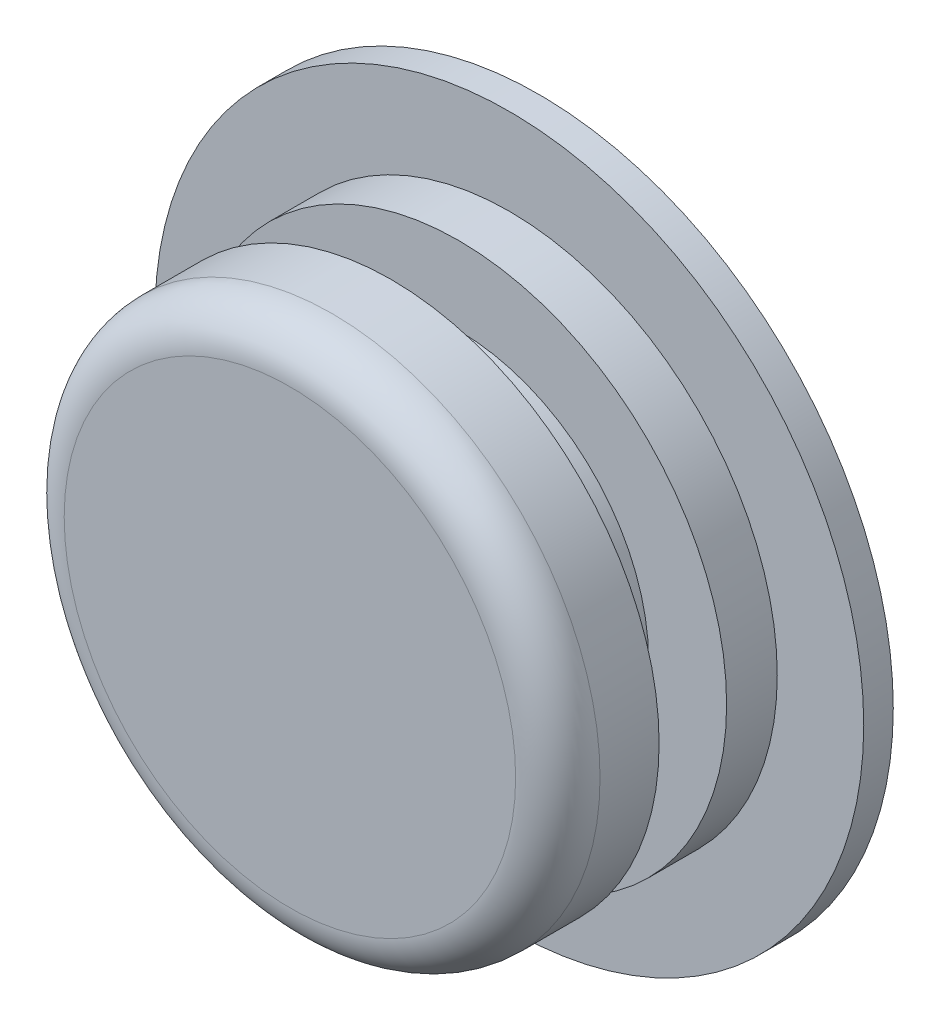
SolidWorks part; units mm, degrees
ref_plane "Alzado" through (0, 0, 0) normal (0, 0, 1) x (1, 0, 0)
ref_plane "Planta" through (0, 0, 0) normal (0, 1, 0) x (1, 0, 0)
ref_plane "Vista lateral" through (0, 0, 0) normal (1, 0, 0) x (0, 0, -1)
sketch "Croquis1" plane through (0, 0, 0) normal (0, 0, 1) x (1, 0, 0)
  circle A0 centre (0, 0) radius 42
  dimension "D1" = 84
extrude "Saliente-Extruir1" add sketch "Croquis1" along normal blind 3.5
sketch "Croquis2" plane through (0, 0, 3.5) normal (0, 0, 1) x (1, 0, 0)
  circle A0 centre (0, 0) radius 31.75
  dimension "D1" = 63.5
extrude "Saliente-Extruir2" add sketch "Croquis2" along normal blind 6
sketch "Croquis3" plane through (0, 0, 9.5) normal (0, 0, 1) x (1, 0, 0)
  circle A0 centre (0, 0) radius 22.5
  dimension "D1" = 45
extrude "Saliente-Extruir3" add sketch "Croquis3" along normal blind 8
sketch "Croquis4" plane through (0, 0, 17.5) normal (0, 0, 1) x (1, 0, 0)
  circle A1 centre (0, 0) radius 31.75
  circle A2 centre (0, 0) radius 31.75
  dimension "D1" = 0
extrude "Saliente-Extruir4" add sketch "Croquis4" along normal blind 12 separate body
fillet "Redondeo1" radius 5 1 edges at (31.75, 0, 29.5)
